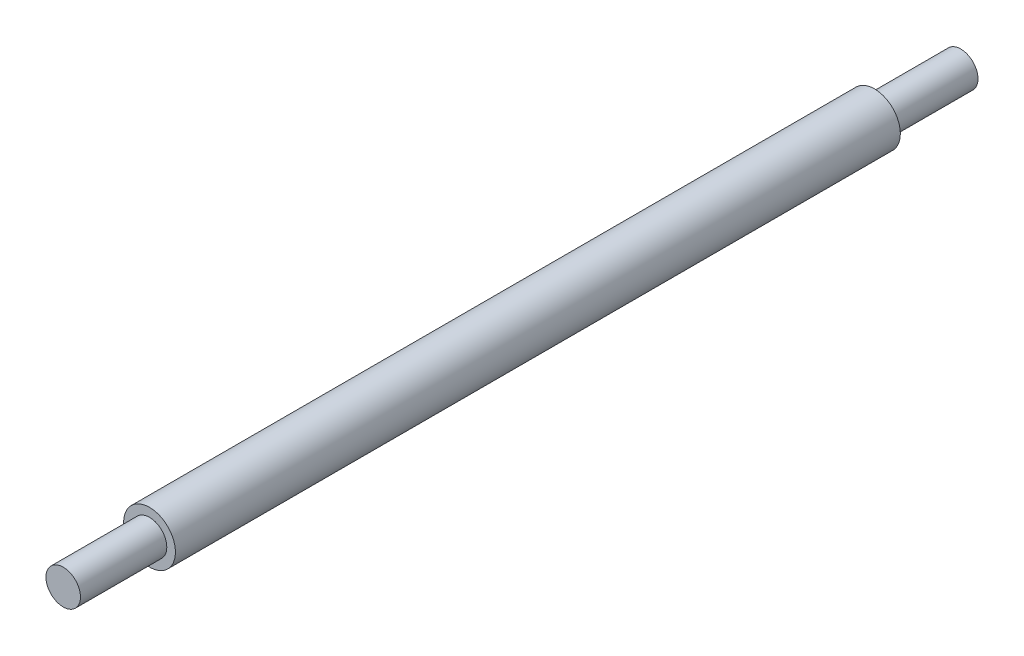
SolidWorks part; units mm, degrees
material "AISI 1020 Steel, Cold Rolled"
ref_plane "Front Plane" through (0, 0, 0) normal (0, 0, 1) x (1, 0, 0)
ref_plane "Top Plane" through (0, 0, 0) normal (0, 1, 0) x (1, 0, 0)
ref_plane "Right Plane" through (0, 0, 0) normal (1, 0, 0) x (0, 0, -1)
sketch "Sketch1" plane through (0, 0, 0) normal (1, 0, 0) x (0, 0, -1)
  line L0 (-68.1176, 0) -> (68.1176, 0) construction
  line L1 (-42, 3) -> (42, 3)
  line L2 (-42, 3) -> (-42, 2)
  line L3 (-42, 2) -> (-52, 2)
  line L4 (-52, 2) -> (-52, 0)
  line L5 (42, 3) -> (42, 2)
  line L6 (42, 2) -> (52, 2)
  line L7 (52, 2) -> (52, 0)
  line L8 (-52, 0) -> (52, 0)
  point P4 (0, 0)
  point P8 (0, 3)
  point P9 (52, 1)
  dimension "D1" = 84
  dimension "D2" = 6
  dimension "D3" = 1
  dimension "D4" = 10
  dimension "D5" = 10
  dimension "D7" = 104
revolve "Revolve1" add sketch "Sketch1" angle 360 about L0
